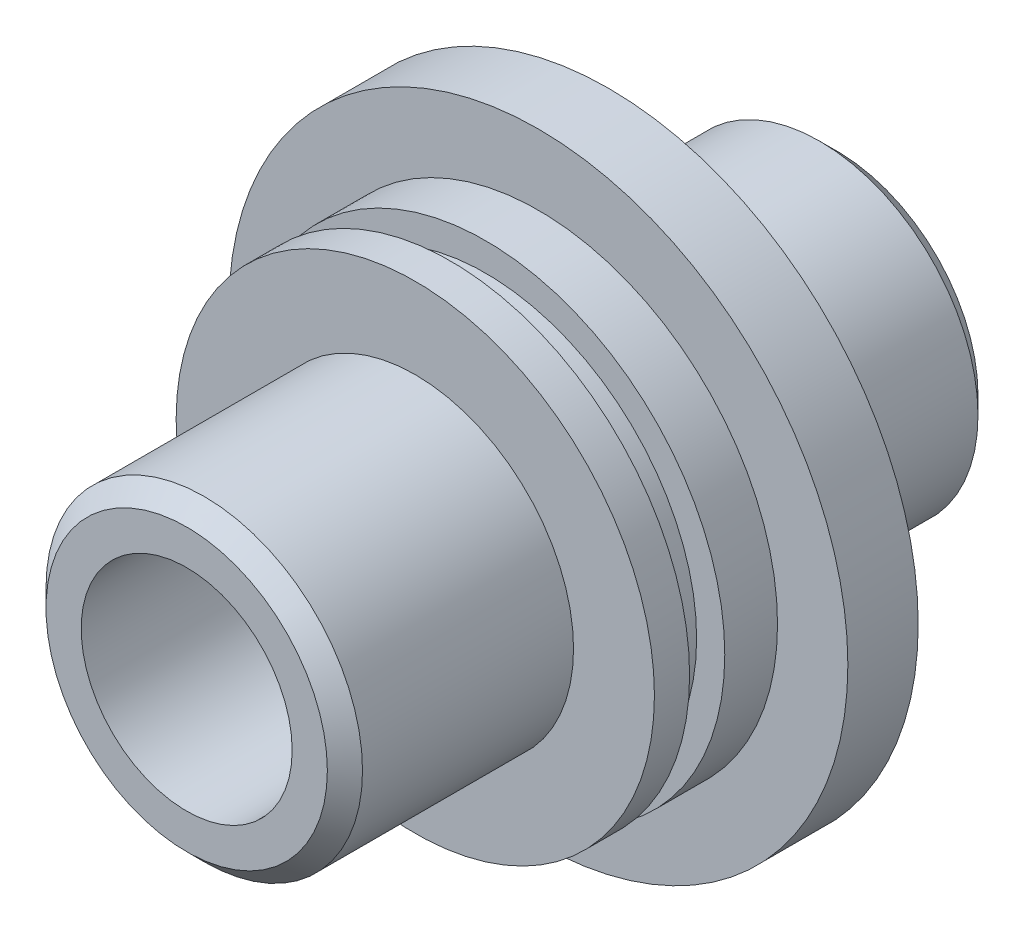
SolidWorks part; units mm, degrees
ref_plane "Front Plane" through (0, 0, 0) normal (0, 0, 1) x (1, 0, 0)
ref_plane "Top Plane" through (0, 0, 0) normal (0, 1, 0) x (1, 0, 0)
ref_plane "Right Plane" through (0, 0, 0) normal (1, 0, 0) x (0, 0, -1)
sketch "Sketch1" plane through (0, 0, 0) normal (0, 0, 1) x (1, 0, 0)
  circle A0 centre (0, 0) radius 8.8
  circle A1 centre (0, 0) radius 3
extrude "Boss-Extrude1" add sketch "Sketch1" along normal blind 18.5
sketch "Sketch2" plane through (0, 0, 18.5) normal (0, 0, 1) x (1, 0, 0)
  circle A0 centre (0, 0) radius 4.5
extrude "Cut-Extrude1" cut sketch "Sketch2" against normal blind 6.5 flip side to cut
sketch "Sketch3" plane through (0, 0, 0) normal (0, 0, -1) x (-1, 0, 0)
  circle A0 centre (0, 0) radius 4.5
extrude "Cut-Extrude2" cut sketch "Sketch3" against normal blind 6.5 flip side to cut
sketch "Sketch4" plane through (0, 0, 12) normal (0, 0, 1) x (1, 0, 0)
  circle A0 centre (0, 0) radius 6.8
extrude "Cut-Extrude3" cut sketch "Sketch4" against normal offset from surface (3.5 mm away) 2 flip side to cut up to face at (-4.5, 0, 6.5)
sketch "Sketch5" plane through (0, 0, 12) normal (0, 0, 1) x (1, 0, 0)
  circle A0 centre (0, 0) radius 6
extrude "Cut-Extrude4" cut sketch "Sketch5" against normal blind 1 from offset 1 flip side to cut offset against normal yes
chamfer "Chamfer1" distance 0.5 angle 45 2 edges at (4.5, 0, 18.5) (-4.5, 0, 0)
